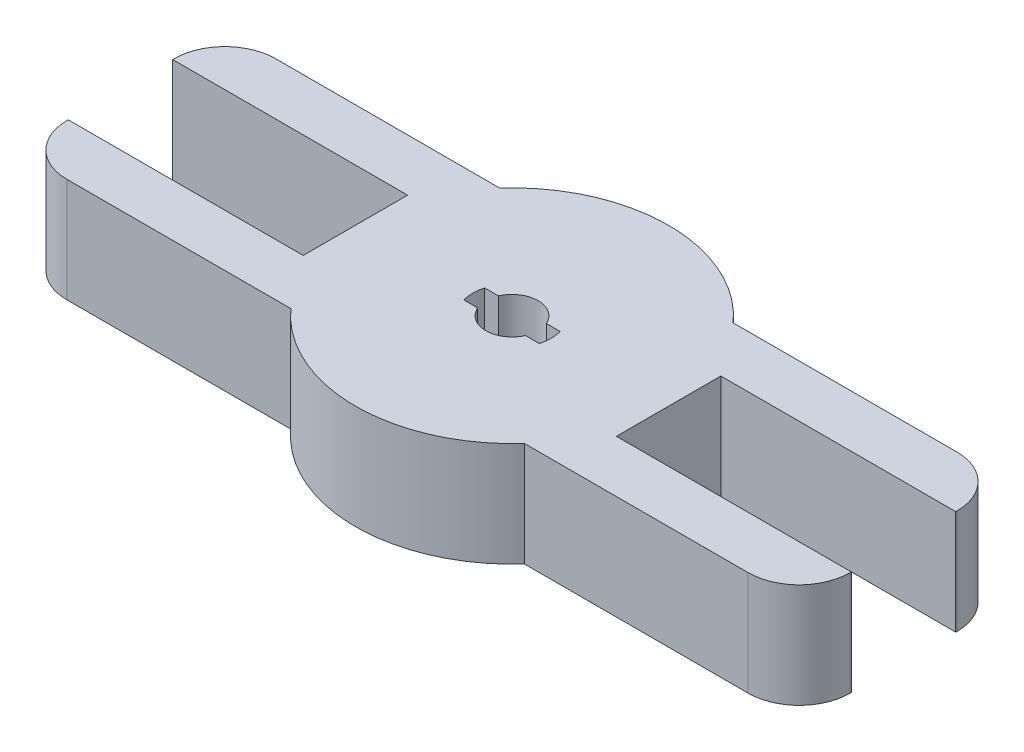
SolidWorks part; units mm, degrees
material "PTFE (general)"
ref_plane "Front Plane" through (0, 0, 0) normal (0, 0, 1) x (1, 0, 0)
ref_plane "Top Plane" through (0, 0, 0) normal (0, 1, 0) x (1, 0, 0)
ref_plane "Right Plane" through (0, 0, 0) normal (1, 0, 0) x (0, 0, -1)
sketch "Sketch1" plane through (0, 0, 0) normal (0, 1, 0) x (1, 0, 0)
  line L0 (22.3607, 20) -> (75, 20)
  line L1 (75, 20) -> (75, -20)
  line L2 (75, -20) -> (22.3607, -20)
  line L3 (0, -20) -> (0, 20)
  line L4 (0, 20) -> (0, 30)
  line L5 (0, -20) -> (0, -30)
  arc A0 (0, -30) -> (22.3607, -20) centre (0, 0) ccw
  arc A1 (22.3607, 20) -> (0, 30) centre (0, 0) ccw
  point P5 (0, 0)
  dimension "D1" = 60
  dimension "D2" = 75
  dimension "D3" = 40
extrude "Boss-Extrude1" add sketch "Sketch1" along normal blind 20
sketch "Sketch2" plane through (0, 20, 0) normal (0, 1, 0) x (1, 0, 0)
  line L0 (0, 5) -> (0, -5)
  line L1 (30, 10) -> (30, -10)
  line L2 (30, -10) -> (75, -10)
  line L3 (75, -10) -> (75, 10)
  line L4 (75, 10) -> (30, 10)
  line L5 (0, 0) -> (30, 0) construction
  line L6 (75, -20) -> (75, 20) construction
  line L7 (7.2284, 2) -> (4.5826, 2)
  line L8 (7.2284, -2) -> (4.5826, -2)
  arc A0 (0, -5) -> (4.5826, -2) centre (0, 0) ccw
  arc A1 (7.2284, -2) -> (7.2284, 2) centre (0, 0) ccw
  arc A2 (4.5826, 2) -> (0, 5) centre (0, 0) ccw
  point P1 (75, 0)
  point P8 (30, 0)
  dimension "D1" = 10
  dimension "D2" = 30
  dimension "D4" = 15
  dimension "D3" = 20
  dimension "D5" = 2
  dimension "D6" = 2
extrude "Cut-Extrude1" cut sketch "Sketch2" against normal up to surface (20 mm away) up to face at (32.8093, 0, 0)
fillet "Fillet1" radius 9.75 2 edges at (75, 10, 20) (75, 10, -20)
sketch "Sketch3" plane through (0, 0, -20) normal (0, 0, -1) x (-1, 0, 0)
  line L0 (0, 20) -> (0, 0) construction
  circle A0 centre (-40, 10) radius 2.5
  circle A1 centre (-50, 10) radius 2.5
  circle A2 centre (-60, 10) radius 2.5
  circle A3 centre (-70, 10) radius 2.5
  circle A4 centre (-80, 10) radius 2.5
  circle A5 centre (-90, 10) radius 2.5
  circle A6 centre (-100, 10) radius 2.5
  point P4 (0, 10)
  dimension "D2" = 5
  dimension "D1" = 40
  dimension "D3" = 7
extrude "Cut-Extrude2" [suppressed] cut sketch "Sketch3" against normal up to surface (40 mm away)
mirror "Mirror4" about plane through (0, 0, 0) normal (1, 0, 0) of "Boss-Extrude1", "Cut-Extrude1", "Fillet1", "Cut-Extrude2"
sketch "Sketch4" plane through (0, 20, 0) normal (0, 1, 0) x (1, 0, 0)
  circle A0 centre (21, 0) radius 2.1
  circle A1 centre (14.8492, -14.8492) radius 2.1
  circle A2 centre (0, -21) radius 2.1
  circle A3 centre (-14.8492, -14.8492) radius 2.1
  circle A4 centre (-21, 0) radius 2.1
  circle A5 centre (-14.8492, 14.8492) radius 2.1
  circle A6 centre (0, 21) radius 2.1
  circle A7 centre (14.8492, 14.8492) radius 2.1
  point P19 (0, 0)
  dimension "D2" = 4.2
  dimension "D1" = 21
  dimension "D3" = 8
extrude "Cut-Extrude3" [suppressed] cut sketch "Sketch4" against normal up to surface (20 mm away)
sketch "Sketch5" plane through (0, 20, 0) normal (0, 1, 0) x (1, 0, 0)
  line L0 (0, 30) -> (0, -30) construction
  line L1 (-30, 0) -> (30, 0) construction
  line L2 (-30, 10) -> (-30, -10) construction
  line L3 (30, 10) -> (30, -10) construction
  arc A0 (22.3607, 20) -> (-22.3607, 20) centre (0, 0) ccw construction
  arc A1 (-22.3607, -20) -> (22.3607, -20) centre (0, 0) ccw construction
fillet "Fillet2" [suppressed] radius 5
